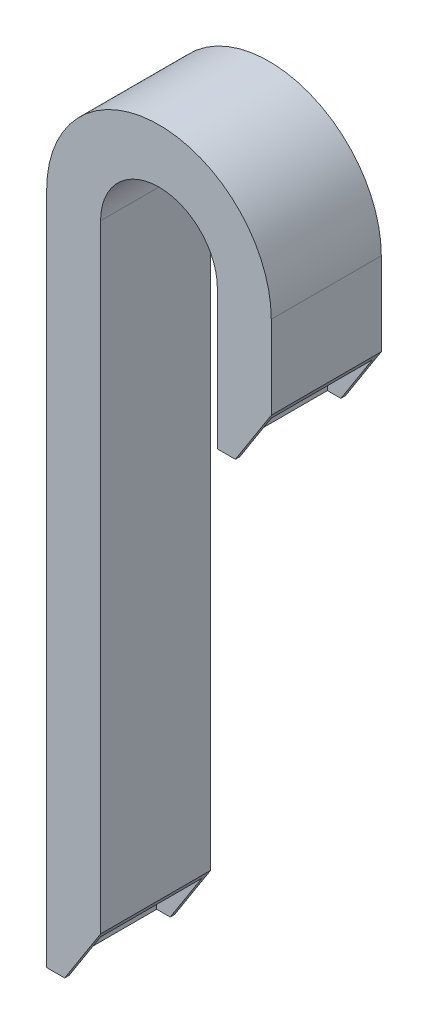
SolidWorks part; units mm, degrees
material "MC尼龙"
ref_plane "前视" through (0, 0, 0) normal (0, 0, 1) x (1, 0, 0)
ref_plane "上视" through (0, 0, 0) normal (0, 1, 0) x (1, 0, 0)
ref_plane "右视" through (0, 0, 0) normal (1, 0, 0) x (0, 0, -1)
sketch "草图1" plane through (0, 0, 0) normal (0, 0, 1) x (1, 0, 0)
  line L0 (0, 0) -> (0, 300)
  line L2 (76, 300) -> (76, 238)
  arc A0 (0, 300) -> (76, 300) centre (38, 300) cw
  dimension "D1" = 300
  dimension "D2" = 76
  dimension "D3" = 100
extrude "拉伸-薄壁1" add sketch "草图1" along normal mid plane 49 thin thin type two direction wall 12 second wall 12
shell "抽壳1" thickness 2
sketch "草图2" plane through (0, 0, 24.5) normal (0, 0, 1) x (1, 0, 0)
  line L0 (88, 263) -> (88, 238)
  line L1 (88, 238) -> (64, 238) construction
  line L2 (72, 238) -> (88, 263)
  line L3 (88, 300) -> (88, 238) construction
  line L4 (88, 238) -> (72, 238)
  line L6 (12, 25) -> (12, 0)
  line L7 (12, 0) -> (-4, 0)
  line L8 (12, 0) -> (-12, 0) construction
  line L9 (-4, 0) -> (12, 25)
  line L10 (12, 0) -> (12, 300) construction
  line L11 (-12, 0) -> (-12, 300) construction
  dimension "D1" = 8
  dimension "D2" = 25
extrude "切除-拉伸1" cut sketch "草图2" against normal through all
hole_wizard "M4 间隙孔1" positions "草图4" profile "草图3" hole size "M4" standard "Gb" end condition through all
sketch "草图4" plane through (-10, 0, 0) normal (1, 0, 0) x (0, 0, -1)
  line L1 (0, 0) -> (0, -12.5327) construction
  line L2 (-22.5, 0) -> (22.5, 0) construction
  point P0 (12.5, 10)
  point P11 (-12.5, 10)
  dimension "D1" = 25
  dimension "D2" = 10
sketch "草图3" plane through (-10, 10, -12.5) normal (0, 1, 0) x (0, 0, -1)
  line L0 (0, 0) -> (0, 2)
  line L1 (0, 2) -> (2.25, 2)
  line L2 (2.25, 2) -> (2.25, 0)
  line L5 (2.25, 0) -> (0, 0)
  line L11 (0, -6.35) -> (0, 107.95) construction
  dimension "通孔孔直径" = 4.5
  dimension "通孔孔深度" = 2
hole_wizard "M4 间隙孔2" positions "草图6" profile "草图5" hole size "M4" standard "Gb"
sketch "草图6" plane through (66, 0, 0) normal (1, 0, 0) x (0, 0, -1)
  line L0 (0, 238) -> (0, 252.0376) construction
  line L1 (-22.5, 238) -> (22.5, 238) construction
  point P0 (12.5, 248)
  point P15 (-12.5, 248)
  dimension "D1" = 10
sketch "草图5" plane through (66, 248, -12.5) normal (0, 1, 0) x (0, 0, -1)
  line L0 (0, 0) -> (0, 2)
  line L1 (0, 2) -> (2.25, 2)
  line L2 (2.25, 2) -> (2.25, 0)
  line L5 (2.25, 0) -> (0, 0)
  line L11 (0, -6.35) -> (0, 107.95) construction
  dimension "通孔孔直径" = 4.5
  dimension "通孔孔深度" = 2
